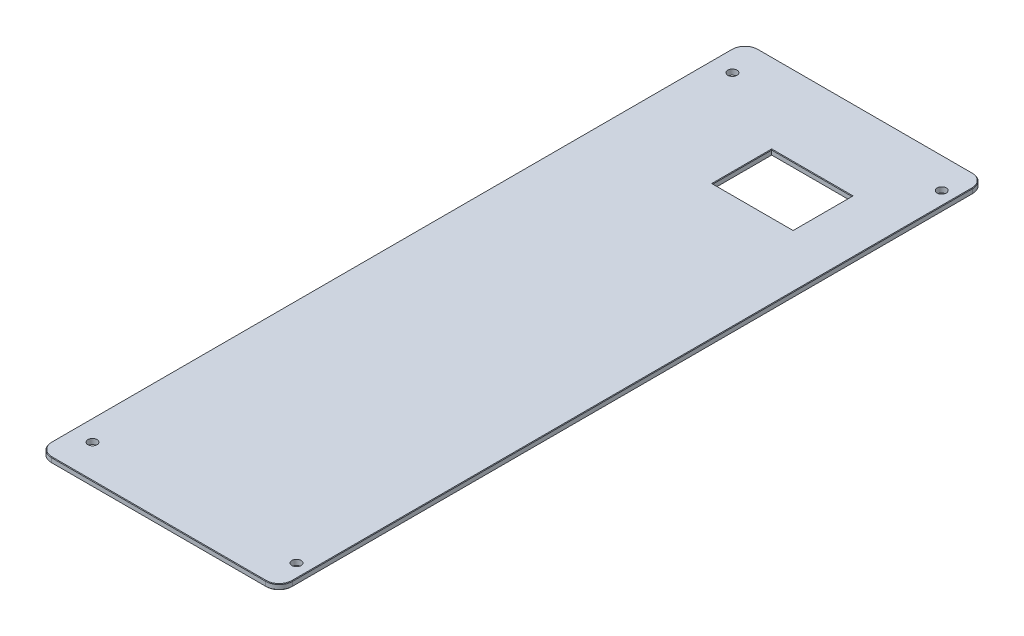
SolidWorks part; units mm, degrees
ref_plane "Plan1" through (0, 0, 0) normal (0, 0, 1) x (1, 0, 0)
ref_plane "Plan2" through (0, 0, 0) normal (0, 1, 0) x (1, 0, 0)
ref_plane "Plan3" through (0, 0, 0) normal (1, 0, 0) x (0, 0, -1)
sketch "Esquisse1" plane through (0, 0, 0) normal (0, 0, 1) x (1, 0, 0)
  line L0 (0, 0) -> (90, 0)
  line L1 (0, 0) -> (0, 2)
  line L2 (90, 2) -> (0, 2)
  line L3 (90, 2) -> (90, 0)
  dimension "D1" = 90
  dimension "D2" = 2
extrude "Base-Extrusion" add sketch "Esquisse1" along normal blind 264
sketch "Esquisse2" plane through (0, 2, 0) normal (0, 1, 0) x (-1, 0, 0)
  line L0 (-70, 52) -> (-40, 52)
  line L1 (-70, 52) -> (-70, 30)
  line L2 (-40, 30) -> (-70, 30)
  line L3 (-40, 30) -> (-40, 52)
  line L5 (-90, 0) -> (0, 0) construction
  line L7 (0, 264) -> (0, 0) construction
  dimension "D1" = 40
  dimension "D2" = 30
  dimension "D3" = 30
  dimension "D4" = 22
extrude "Enlèv. mat.-Extru.1" cut sketch "Esquisse2" against normal through all
sketch "Esquisse3" plane through (0, 2, 0) normal (0, 1, 0) x (-1, 0, 0)
  line L0 (-7.82, 270) -> (-7.82, -10) construction
  line L1 (-85, 270) -> (-85, -10) construction
  line L2 (0, 264) -> (-90, 264) construction
  line L3 (-90, 264) -> (-90, 0) construction
  line L4 (-90, 0) -> (0, 0) construction
  line L5 (0, 264) -> (0, 0) construction
  circle A0 centre (-7.82, 251.51) radius 1.7
  circle A1 centre (-7.82, 12.49) radius 1.7
  circle A2 centre (-85, 252.5) radius 1.7
  circle A3 centre (-85, 11.5) radius 1.7
  dimension "D1" = 3.4
  dimension "D4" = 11.5
  dimension "D5" = 241
  dimension "D6" = 239.02
  dimension "D7" = 12.49
  dimension "D2" = 7.82
  dimension "D3" = 5
fillet "Congé1" radius 5
chamfer "Chanfrein1" distance 0.2 angle 45
extrude "Enlèv. mat.-Extru.2" cut sketch "Esquisse3" against normal through all
